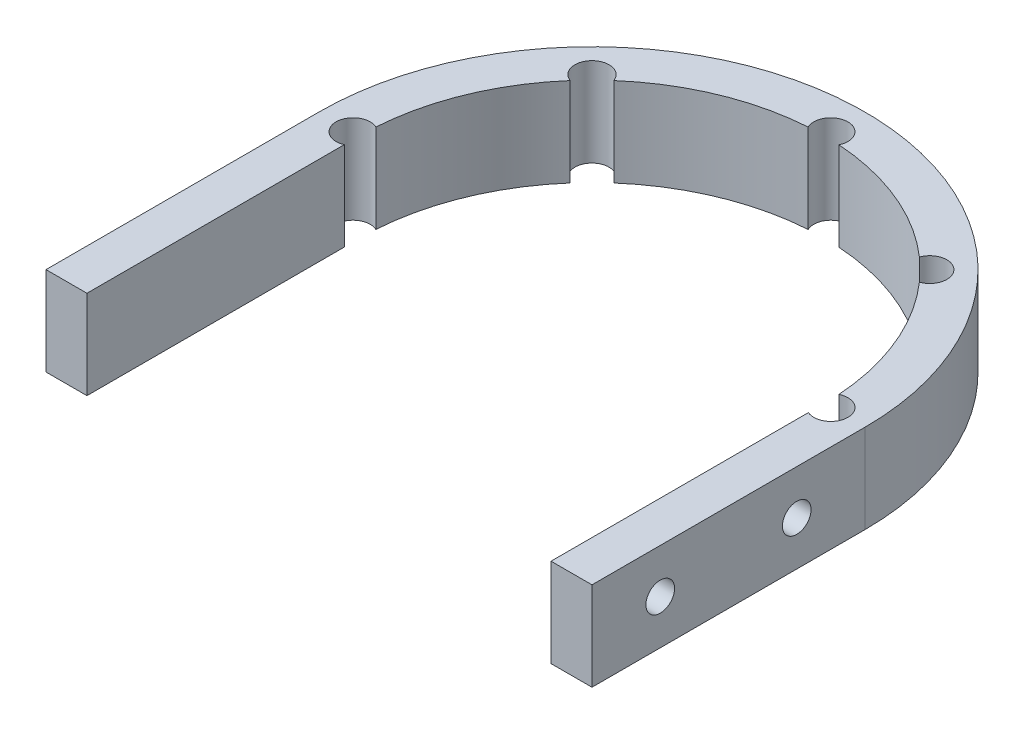
SolidWorks part; units mm, degrees
ref_plane "前视基准面" through (0, 0, 0) normal (0, 0, 1) x (1, 0, 0)
ref_plane "上视基准面" through (0, 0, 0) normal (0, 1, 0) x (1, 0, 0)
ref_plane "右视基准面" through (0, 0, 0) normal (1, 0, 0) x (0, 0, -1)
other "Configuration Table"
sketch "草图1" plane through (0, 0, 0) normal (0, 1, 0) x (1, 0, 0)
  line L2 (-40, 0) -> (-40, -40)
  line L3 (-40, -40) -> (40, -40)
  line L4 (40, 0) -> (40, -40)
  arc A0 (40, 0) -> (-40, 0) centre (0, 0) ccw
  circle A1 centre (0, 0) radius 34
  dimension "D1" = 80
  dimension "D2" = 68
extrude "凸台-拉伸1" add sketch "草图1" along normal blind 13
sketch "草图2" plane through (0, 13, 0) normal (0, 1, 0) x (1, 0, 0)
  circle A0 centre (0, 0) radius 35 construction
  circle A1 centre (0, 35) radius 2.5
  circle A2 centre (24.7487, 24.7487) radius 2.5
  circle A3 centre (35, 0) radius 2.5
  circle A4 centre (24.7487, -24.7487) radius 2.5
  circle A5 centre (0, -35) radius 2.5
  circle A6 centre (-24.7487, -24.7487) radius 2.5
  circle A7 centre (-35, 0) radius 2.5
  circle A8 centre (-24.7487, 24.7487) radius 2.5
  point P21 (0, 0)
  dimension "D1" = 70
  dimension "D2" = 5
  dimension "D3" = 8
extrude "切除-拉伸1" cut sketch "草图2" against normal through all
sketch "草图3" plane through (0, 13, 0) normal (0, 1, 0) x (1, 0, 0)
  line L0 (-40, -40) -> (40, -40) construction
  line L1 (-34, -40) -> (34, -40)
  line L2 (-34, -40) -> (-34, 0)
  line L3 (-34, 0) -> (34, 0)
  line L4 (34, -40) -> (34, 0)
  line L5 (-35, 0) -> (35, 0) construction
  arc A0 (-25.5846, 22.3926) -> (-33.925, 2.2571) centre (0, 0) ccw construction
  arc A1 (33.925, 2.2571) -> (25.5846, 22.3926) centre (0, 0) ccw construction
extrude "切除-拉伸2" cut sketch "草图3" against normal through all
sketch "草图4" plane through (-40, 0, 0) normal (-1, 0, 0) x (0, 0, 1)
  line L0 (0, 6.5) -> (40, 6.5) construction
  line L1 (0, 13) -> (0, 0) construction
  line L2 (40, 13) -> (40, 0) construction
  circle A0 centre (10, 6.5) radius 2.1
  circle A1 centre (30, 6.5) radius 2.1
  point P10 (20, 6.5)
  dimension "D1" = 4.2
  dimension "D2" = 4.2
  dimension "D3" = 10
  dimension "D4" = 10
extrude "切除-拉伸3" cut sketch "草图4" against normal blind 4
ref_plane "基准面1" through (0, 0, 0) normal (-1, 0, 0) x (0, 0, 1)
mirror "镜向1" about plane through (0, 0, 0) normal (-1, 0, 0) of "切除-拉伸3"
